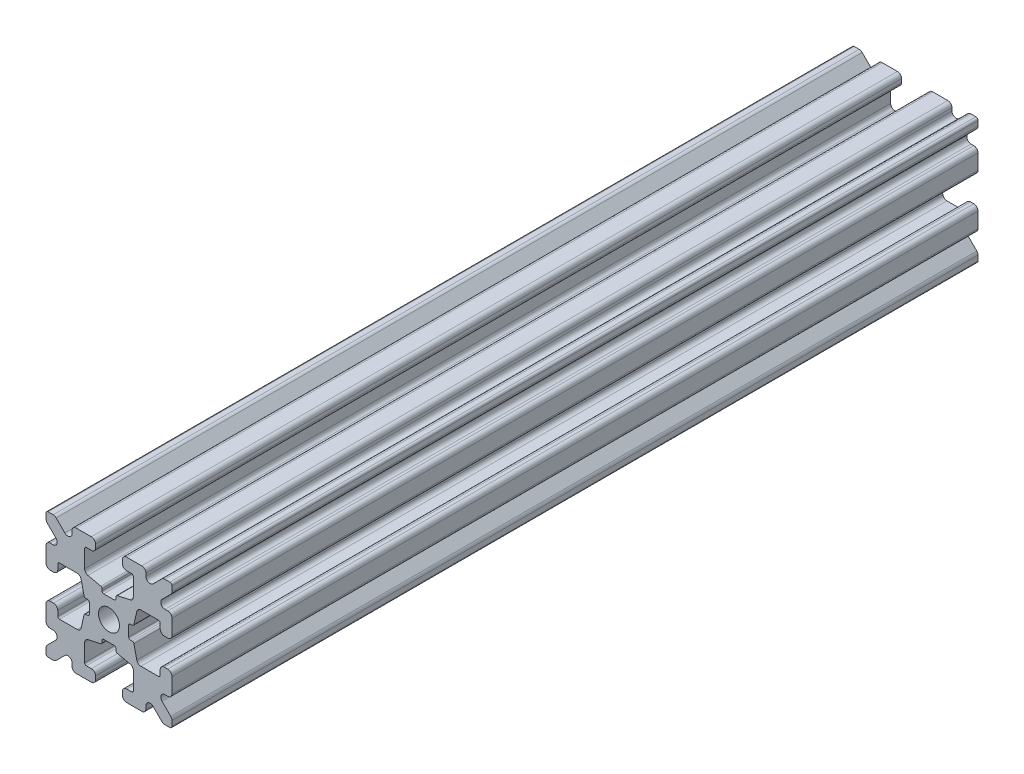
SolidWorks part; units mm, degrees
ref_plane "Front Plane" through (0, 0, 0) normal (0, 0, 1) x (1, 0, 0)
ref_plane "Top Plane" through (0, 0, 0) normal (0, 1, 0) x (1, 0, 0)
ref_plane "Right Plane" through (0, 0, 0) normal (1, 0, 0) x (0, 0, -1)
sketch "Sketch1" plane through (0, 0, 0) normal (0, 0, 1) x (1, 0, 0)
  line L1 (-7.5, -7.5) -> (7.5, -7.5)
  line L2 (-7.5, -7.5) -> (-7.5, 7.5)
  line L3 (-7.5, 7.5) -> (7.5, 7.5)
  line L4 (7.5, -7.5) -> (7.5, 7.5)
  line L5 (-7.5, -7.5) -> (7.5, 7.5) construction
  line L6 (-7.5, 7.5) -> (7.5, -7.5) construction
  circle A0 centre (0, 0) radius 1.25
  point P0 (0, 0)
  dimension "D2" = 2.5
  dimension "D1" = 15
extrude "Boss-Extrude1" add sketch "Sketch1" along normal mid plane 96
fillet "Fillet1" radius 0.25 4 edges at (7.5, -7.5, 0) (-7.5, -7.5, 0) (7.5, 7.5, 0) (-7.5, 7.5, 0)
sketch "Sketch2" plane through (0, 0, 48) normal (0, 0, 1) x (1, 0, 0)
  line L0 (-7.5, 7.25) -> (-7.5, -7.25) construction
  line L1 (-7.5, 1.6) -> (-6.1, 1.6)
  line L2 (-7.5, 1.6) -> (-7.5, -1.6)
  line L3 (-7.5, -1.6) -> (-6.1, -1.6)
  line L4 (-6.1, 1.6) -> (-6.1, 2.9)
  line L5 (0, 0) -> (-12.1036, 0) construction
  line L6 (-6.1, -2.9) -> (-3.4, -2.9)
  line L7 (0, 0) -> (-7.25, 7.25) construction
  line L8 (-6.1, 2.9) -> (-3.4, 2.9)
  line L9 (-3.4, -2.9) -> (-3.4, 2.9)
  line L10 (55, 0) -> (-55, 0) construction
  line L11 (-6.1, -2.9) -> (-6.1, -1.6)
  line L12 (2.9, 6.1) -> (1.6, 6.1)
  line L13 (2.9, 3.4) -> (-2.9, 3.4)
  line L14 (-2.9, 6.1) -> (-2.9, 3.4)
  line L15 (2.9, 6.1) -> (2.9, 3.4)
  line L16 (-1.6, 6.1) -> (-2.9, 6.1)
  line L17 (1.6, 7.5) -> (1.6, 6.1)
  line L18 (-1.6, 7.5) -> (1.6, 7.5)
  line L19 (-1.6, 7.5) -> (-1.6, 6.1)
  line L20 (-1.6, -7.5) -> (-1.6, -6.1)
  line L21 (-1.6, -7.5) -> (1.6, -7.5)
  line L22 (1.6, -7.5) -> (1.6, -6.1)
  line L23 (-1.6, -6.1) -> (-2.9, -6.1)
  line L24 (2.9, -6.1) -> (2.9, -3.4)
  line L25 (-2.9, -6.1) -> (-2.9, -3.4)
  line L26 (2.9, -3.4) -> (-2.9, -3.4)
  line L27 (2.9, -6.1) -> (1.6, -6.1)
  line L28 (6.1, -2.9) -> (6.1, -1.6)
  line L29 (3.4, -2.9) -> (3.4, 2.9)
  line L30 (6.1, 2.9) -> (3.4, 2.9)
  line L31 (6.1, -2.9) -> (3.4, -2.9)
  line L32 (6.1, 1.6) -> (6.1, 2.9)
  line L33 (7.5, -1.6) -> (6.1, -1.6)
  line L34 (7.5, 1.6) -> (7.5, -1.6)
  line L35 (7.5, 1.6) -> (6.1, 1.6)
  dimension "D1" = 3.2
  dimension "D2" = 5.8
  dimension "D3" = 1.4
  dimension "D4" = 2.7
extrude "Cut-Extrude1" cut sketch "Sketch2" against normal through all
sketch "Sketch4" plane through (0, 0, 48) normal (0, 0, 1) x (1, 0, 0)
  line L0 (-3.4, 2.9) -> (-2.75, 0)
  line L1 (55, 0) -> (-55, 0) construction
  line L2 (-2.75, 0) -> (-3.4, -2.9)
  line L3 (-3.4, -2.9) -> (-3.4, 2.9) construction
  line L4 (-3.4, 2.9) -> (-3.4, -2.9)
  line L5 (-2.9, 3.4) -> (0, 2.75)
  line L6 (0, 2.75) -> (2.9, 3.4)
  line L7 (2.9, 3.4) -> (-2.9, 3.4)
  line L8 (3.4, 2.9) -> (2.75, 0)
  line L9 (2.75, 0) -> (3.4, -2.9)
  line L10 (3.4, -2.9) -> (3.4, 2.9)
  line L11 (-2.9, -3.4) -> (0, -2.75)
  line L12 (0, -2.75) -> (2.9, -3.4)
  line L13 (2.9, -3.4) -> (-2.9, -3.4)
  circle A2 centre (0, 0) radius 2.75
  circle A3 centre (0, 0) radius 2.75 construction
  dimension "D1" = 1.5
extrude "Cut-Extrude3" cut sketch "Sketch4" against normal through all
fillet "Fillet3" radius 0.5 16 edges at (-6.1, -1.6, 0) (-7.5, -1.6, 0) (-6.1, 1.6, 0) (-7.5, 1.6, 0) (-1.6, -7.5, 0) (-1.6, -6.1, 0) (1.6, -7.5, 0) (1.6, -6.1, 0) (6.1, -1.6, 0) (7.5, -1.6, 0) (7.5, 1.6, 0) (6.1, 1.6, 0) (1.6, 7.5, 0) (1.6, 6.1, 0) (-1.6, 7.5, 0) (-1.6, 6.1, 0)
fillet "Fillet4" radius 0.5 8 edges at (-3.4, 2.9, 0) (-3.4, -2.9, 0) (2.9, -3.4, 0) (-2.9, -3.4, 0) (3.4, -2.9, 0) (3.4, 2.9, 0) (-2.9, 3.4, 0) (2.9, 3.4, 0)
fillet "Fillet5" radius 3 4 edges at (0, -2.75, 0) (2.75, 0, 0) (-2.75, 0, 0) (0, 2.75, 0)
fillet "Fillet6" radius 0.2 8 edges at (-2.9, -6.1, 0) (2.9, -6.1, 0) (6.1, -2.9, 0) (6.1, 2.9, 0) (2.9, 6.1, 0) (-2.9, 6.1, 0) (-6.1, -2.9, 0) (-6.1, 2.9, 0)
sketch "Sketch5" plane through (0, 0, 48) normal (0, 0, 1) x (1, 0, 0)
  line L0 (0, 0) -> (-7.25, 7.25) construction
  line L1 (-7.5, 6.4393) -> (-5.4607, 4.4)
  line L2 (-6.4393, 7.5) -> (-4.4, 5.4607)
  line L3 (-7.5, 4.4) -> (-5.4607, 4.4)
  line L4 (-3.8003, 2.9) -> (-5.9, 2.9) construction
  line L5 (0, 0) -> (-12.1819, 0) construction
  line L6 (-4.4, 7.5) -> (-4.4, 5.4607)
  line L7 (-2.9, 5.9) -> (-2.9, 3.8003) construction
  line L8 (-7.5, 6.4393) -> (-7.5, 4.4)
  line L9 (-7.5, 7.25) -> (-7.5, 2.1) construction
  line L10 (2.1, -7.5) -> (7.25, -7.5) construction
  line L11 (7.5, -7.25) -> (7.5, -2.1) construction
  line L12 (7.25, 7.5) -> (2.1, 7.5) construction
  line L13 (-2.1, 7.5) -> (-7.25, 7.5) construction
  line L14 (-4.4, 7.5) -> (-6.4393, 7.5)
  line L16 (55, 0) -> (-55, 0) construction
  line L17 (0, 0) -> (0, 10.993) construction
  line L18 (0, -54.6431) -> (0, 54.6431) construction
  line L20 (4.4, 7.5) -> (6.4393, 7.5)
  line L22 (7.5, 6.4393) -> (7.5, 4.4)
  line L23 (4.4, 7.5) -> (4.4, 5.4607)
  line L24 (7.5, 4.4) -> (5.4607, 4.4)
  line L25 (6.4393, 7.5) -> (4.4, 5.4607)
  line L26 (7.5, 6.4393) -> (5.4607, 4.4)
  line L27 (7.5, -6.4393) -> (5.4607, -4.4)
  line L28 (6.4393, -7.5) -> (4.4, -5.4607)
  line L29 (7.5, -4.4) -> (5.4607, -4.4)
  line L30 (4.4, -7.5) -> (4.4, -5.4607)
  line L31 (7.5, -6.4393) -> (7.5, -4.4)
  line L33 (4.4, -7.5) -> (6.4393, -7.5)
  line L36 (-4.4, -7.5) -> (-6.4393, -7.5)
  line L38 (-7.5, -6.4393) -> (-7.5, -4.4)
  line L39 (-4.4, -7.5) -> (-4.4, -5.4607)
  line L40 (-7.5, -4.4) -> (-5.4607, -4.4)
  line L41 (-6.4393, -7.5) -> (-4.4, -5.4607)
  line L42 (-7.5, -6.4393) -> (-5.4607, -4.4)
  dimension "D1" = 1.5
  dimension "D2" = 1.5
  dimension "D3" = 1.5
extrude "Cut-Extrude4" cut sketch "Sketch5" against normal through all
fillet "Fillet8" radius 0.5 24 edges at (-5.4607, 4.4, 0) (-7.5, 4.4, 0) (-5.4607, -4.4, 0) (-7.5, -4.4, 0) (-4.4, -7.5, 0) (-4.4, -5.4607, 0) (4.4, -7.5, 0) (4.4, -5.4607, 0) (5.4607, -4.4, 0) (7.5, -4.4, 0) (7.5, 4.4, 0) (5.4607, 4.4, 0) (4.4, 5.4607, 0) (4.4, 7.5, 0) (-4.4, 5.4607, 0) (-4.4, 7.5, 0) (-6.4393, 7.5, 0) (-7.5, 6.4393, 0) (6.4393, 7.5, 0) (7.5, 6.4393, 0) (6.4393, -7.5, 0) (7.5, -6.4393, 0) (-6.4393, -7.5, 0) (-7.5, -6.4393, 0)
sketch "Sketch6" plane through (0, 0, 48) normal (0, 0, 1) x (1, 0, 0)
  line L0 (0, 0) -> (0, 11.013) construction
  line L1 (0.6561, 2.8971) -> (2.1235, 2.8971) construction
  line L2 (0, -54.6431) -> (0, 54.6431) construction
  line L3 (0, 0) -> (7.25, 7.25) construction
  line L4 (7.5, 0.8255) -> (7.5, -0.8255)
  line L5 (2.3471, 0.8255) -> (7.5, 0.8255)
  line L6 (0, 0) -> (12.4016, 0) construction
  line L7 (0.8255, -7.5) -> (-0.8255, -7.5)
  line L8 (2.3471, -0.8255) -> (2.3471, 0.8255)
  line L9 (0.8255, -2.3471) -> (0.8255, -7.5)
  line L10 (7.5, -0.8255) -> (2.3471, -0.8255)
  line L11 (-7.5, -0.8255) -> (-2.3471, -0.8255)
  line L12 (-2.3471, -0.8255) -> (-2.3471, 0.8255)
  line L13 (-0.8255, -2.3471) -> (0.8255, -2.3471)
  line L14 (-0.8255, 7.5) -> (-0.8255, 2.3471)
  line L15 (-0.8255, 2.3471) -> (0.8255, 2.3471)
  line L16 (-0.8255, -7.5) -> (-0.8255, -2.3471)
  line L17 (0.8255, 2.3471) -> (0.8255, 7.5)
  line L18 (0.8255, 7.5) -> (-0.8255, 7.5)
  line L19 (3.9, 7.5) -> (2.1, 7.5) construction
  line L20 (-2.3471, 0.8255) -> (-7.5, 0.8255)
  line L21 (-7.5, 0.8255) -> (-7.5, -0.8255)
  point P5 (0, -2.5973)
  point P7 (0, 2.5973)
  dimension "D3" = 0.55
  dimension "D1" = 1.651
extrude "Cut-Extrude5" cut sketch "Sketch6" against normal through all
fillet "Fillet10" radius 0.2 16 edges at (-2.935, 0.8255, 0) (-2.935, -0.8255, 0) (2.935, -0.8255, 0) (2.935, 0.8255, 0) (0.8255, 2.935, 0) (-0.8255, 2.935, 0) (-2.3471, 0.8255, 0) (-2.3471, -0.8255, 0) (0.8255, 2.3471, 0) (-0.8255, 2.3471, 0) (2.3471, 0.8255, 0) (2.3471, -0.8255, 0) (0.8255, -2.935, 0) (0.8255, -2.3471, 0) (-0.8255, -2.3471, 0) (-0.8255, -2.935, 0)
